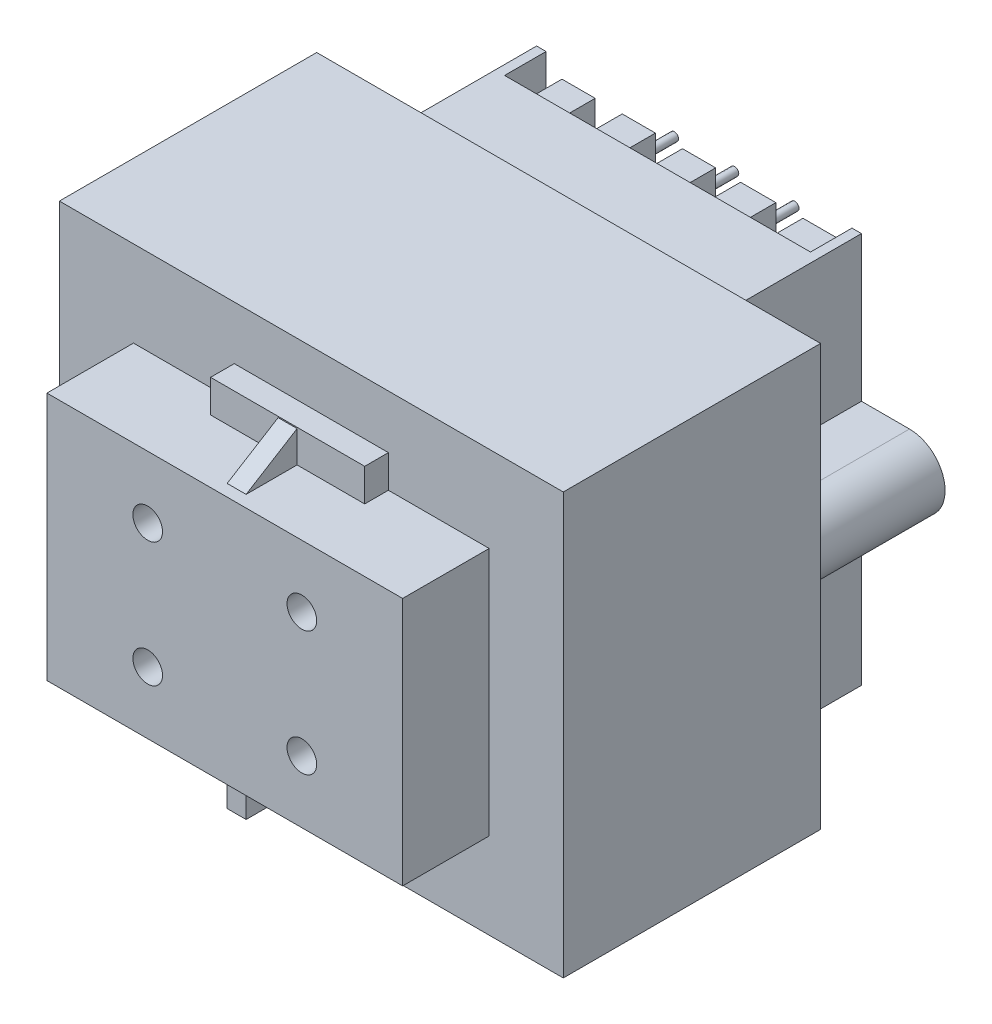
SolidWorks part; units mm, degrees
ref_plane "Спереди" through (0, 0, 0) normal (0, 0, 1) x (1, 0, 0)
ref_plane "Сверху" through (0, 0, 0) normal (0, 1, 0) x (1, 0, 0)
ref_plane "Справа" through (0, 0, 0) normal (1, 0, 0) x (0, 0, -1)
sketch "Эскиз1" plane through (0, 0, 0) normal (0, 0, 1) x (1, 0, 0)
  line L0 (-46.8652, 0) -> (48.3577, 0) construction
  line L1 (0, 0) -> (0, 50.638) construction
  line L3 (-21.25, -17.75) -> (21.25, -17.75)
  line L4 (-21.25, -17.75) -> (-21.25, 17.75)
  line L5 (-21.25, 17.75) -> (21.25, 17.75)
  line L6 (21.25, -17.75) -> (21.25, 17.75)
  dimension "D1" = 42.5
  dimension "D2" = 35.5
extrude "Вытянуть1" add sketch "Эскиз1" along normal blind 40
sketch "Эскиз2" plane through (0, 0, 40) normal (0, 0, 1) x (1, 0, 0)
  line L0 (0, -4.5156) -> (0, 6.793) construction
  line L1 (-5.8899, 0) -> (6.9108, 0) construction
  line L3 (-15, -10.5) -> (15, -10.5)
  line L4 (-21.25, 17.75) -> (-21.25, -17.75)
  line L5 (-21.25, -17.75) -> (21.25, -17.75)
  line L6 (21.25, -17.75) -> (21.25, 17.75)
  line L7 (21.25, 17.75) -> (-21.25, 17.75)
  line L8 (-21.25, 17.75) -> (-21.25, -17.75)
  line L9 (-21.25, -17.75) -> (21.25, -17.75)
  line L10 (21.25, -17.75) -> (21.25, 17.75)
  line L11 (21.25, 17.75) -> (-21.25, 17.75)
  line L12 (-15, -10.5) -> (-15, 10.5)
  line L13 (-15, 10.5) -> (15, 10.5)
  line L14 (15, -10.5) -> (15, 10.5)
  dimension "D2" = 30
  dimension "D3" = 21
  dimension "D1" = 0
extrude "Вырез-Вытянуть1" cut sketch "Эскиз2" against normal blind 7.3
sketch "Эскиз3" plane through (0, 0, 32.7) normal (0, 0, 1) x (1, 0, 0)
  line L0 (0, 0) -> (0, 16.3881) construction
  line L1 (0, 0) -> (13.3068, 0) construction
  line L2 (-6.5, -13.25) -> (6.5, -13.25)
  line L3 (-6.5, -13.25) -> (-6.5, 13.25)
  line L4 (-6.5, 13.25) -> (6.5, 13.25)
  line L5 (6.5, -13.25) -> (6.5, 13.25)
  dimension "D1" = 13
  dimension "D2" = 26.5
extrude "Вытянуть2" add sketch "Эскиз3" along normal blind 2
sketch "Эскиз4" plane through (0, 0, 0) normal (1, 0, 0) x (0, 0, -1)
  line L1 (-34.7, 10.5) -> (-39, 10.5)
  line L2 (-34.7, 10.5) -> (-34.7, 13.1539)
  line L3 (-39, -10.5) -> (-39, -13.25)
  line L4 (-39, -13.25) -> (-34.7, -13.25)
  line L5 (-34.7, -13.25) -> (-34.7, -10.5) construction
  line L6 (-32.7, 10.5) -> (-40, 10.5) construction
  line L7 (-32.7, -10.5) -> (-40, -10.5) construction
  line L8 (-34.7, -10.5) -> (-39, -10.5)
  line L9 (-34.7, -13.25) -> (-34.7, -10.5)
  line L11 (-39, 10.5) -> (-34.7, 13.1539)
extrude "Вытянуть3" add sketch "Эскиз4" along normal blind 0.8 and the other way blind 0.8
sketch "Эскиз5" plane through (0, 0, 40) normal (0, 0, 1) x (1, 0, 0)
  line L0 (0, 0) -> (14.0158, 0) construction
  line L1 (0, 0) -> (0, 9.0803) construction
  circle A0 centre (-6.5, 5.25) radius 1.25
  circle A1 centre (6.5, 5.25) radius 1.25
  circle A2 centre (6.5, -5.25) radius 1.25
  circle A3 centre (-6.5, -5.25) radius 1.25
  dimension "D1" = 2.5
  dimension "D2" = 10.5
  dimension "D3" = 13
extrude "Вырез-Вытянуть2" cut sketch "Эскиз5" against normal blind 2
sketch "Эскиз6" plane through (0, 0, 0) normal (0, 0, -1) x (-1, 0, 0)
  line L0 (-7.8303, 0) -> (7.2418, 0) construction
  line L1 (0, 15.7337) -> (0, -14.6975) construction
  line L2 (-17.75, 4.25) -> (-13.7, 4.25)
  line L3 (-13.7, -16.5) -> (13.7, -16.5)
  line L4 (-13.7, -16.5) -> (-13.7, -1.75)
  line L5 (-13.7, 16.5) -> (13.7, 16.5)
  line L6 (13.7, -16.5) -> (13.7, -1.75)
  line L7 (-17.75, -1.75) -> (-13.7, -1.75)
  line L8 (-13.7, 4.25) -> (-13.7, 16.5)
  line L9 (13.7, 4.25) -> (13.7, 16.5)
  line L10 (21.25, -17.75) -> (21.25, 17.75)
  line L11 (21.25, 17.75) -> (-21.25, 17.75)
  line L12 (-21.25, 17.75) -> (-21.25, -17.75)
  line L13 (-21.25, -17.75) -> (21.25, -17.75)
  line L14 (21.25, -17.75) -> (21.25, 17.75)
  line L15 (21.25, 17.75) -> (-21.25, 17.75)
  line L16 (-21.25, 17.75) -> (-21.25, -17.75)
  line L17 (-21.25, -17.75) -> (21.25, -17.75)
  line L18 (13.7, 4.25) -> (17.75, 4.25)
  line L19 (13.7, -1.75) -> (17.75, -1.75)
  line L20 (-17.75, 1.25) -> (-17.75, 5.963) construction
  arc A0 (-17.75, 4.25) -> (-17.75, -1.75) centre (-17.75, 1.25) ccw
  arc A1 (17.75, -1.75) -> (17.75, 4.25) centre (17.75, 1.25) ccw
  dimension "D4" = 41.5
  dimension "D5" = 6
  dimension "D6" = 13.5
  dimension "D1" = 33
  dimension "D2" = 27.4
  dimension "D3" = 0
extrude "Вырез-Вытянуть3" cut sketch "Эскиз6" against normal blind 11
sketch "Эскиз7" plane through (0, 0, 0) normal (0, 0, -1) x (-1, 0, 0)
  line L0 (-17.75, 1.25) -> (18.26, 1.25) construction
  line L1 (0, 0) -> (0, 11.9161) construction
  line L3 (16, 0) -> (16, 2.5)
  line L4 (-18.5, 0) -> (-16, 0)
  line L5 (-18.5, 0) -> (-18.5, 2.5)
  line L6 (-18.5, 2.5) -> (-16, 2.5)
  line L7 (-16, 0) -> (-16, 2.5)
  line L8 (18.5, 2.5) -> (16, 2.5)
  line L9 (18.5, 0) -> (18.5, 2.5)
  line L10 (18.5, 0) -> (16, 0)
  dimension "D1" = 2.5
  dimension "D2" = 32
extrude "Вырез-Вытянуть4" cut sketch "Эскиз7" against normal blind 8
sketch "Эскиз8" plane through (0, 0, 0) normal (0, 0, -1) x (-1, 0, 0)
  line L0 (-13.7, -16.5) -> (13.7, -16.5) construction
  line L1 (0, 9.0803) -> (0, -16.3881) construction
  line L2 (-13.7, 16.5) -> (-13.7, 4.25) construction
  line L3 (-12.9, 6.25) -> (12.9, 6.25)
  line L4 (-12.9, 6.25) -> (-12.9, 10.5)
  line L5 (-12.9, 10.5) -> (12.9, 10.5)
  line L6 (12.9, 6.25) -> (12.9, 10.5)
  line L7 (13.7, 4.25) -> (13.7, 16.5) construction
  line L8 (-12.9, -10.5) -> (12.9, -10.5)
  line L9 (12.9, -10.5) -> (12.9, -3.75)
  line L10 (-12.9, -3.75) -> (12.9, -3.75)
  line L11 (-12.9, -10.5) -> (-12.9, -3.75)
  line L14 (16, 1.25) -> (1.4009, 1.25) construction
  line L15 (16, 2.5) -> (16, 0) construction
  dimension "D1" = 5
  dimension "D2" = 0.8
  dimension "D3" = 0.8
  dimension "D4" = 10.5
  dimension "D6" = 6
  dimension "D7" = 5
extrude "Вырез-Вытянуть5" cut sketch "Эскиз8" against normal blind 11
sketch "Эскиз9" plane through (0, 0, 0) normal (0, 0, -1) x (-1, 0, 0)
  line L0 (-11.0474, 0) -> (12.9883, 0) construction
  line L1 (0, 0) -> (0, 19.7633) construction
  line L2 (13.7, 16.5) -> (-13.7, 16.5) construction
  line L3 (12.9, 16.5) -> (-12.9, 16.5)
  line L4 (-12.9, 10.5) -> (-12.9, 16.5)
  line L6 (12.1, 15.15) -> (12.1, 10.5)
  line L7 (-12.1, 15.15) -> (12.1, 15.15)
  line L8 (12.1, 10.5) -> (12.9, 10.5)
  line L9 (-12.1, 15.15) -> (-12.1, 10.5)
  line L10 (-12.1, 10.5) -> (-12.9, 10.5)
  line L11 (12.9, 10.5) -> (12.9, 16.5)
  line L12 (12.9, -10.5) -> (12.9, -16.5)
  line L13 (-12.1, -10.5) -> (-12.9, -10.5)
  line L14 (-12.1, -15.15) -> (-12.1, -10.5)
  line L15 (12.1, -10.5) -> (12.9, -10.5)
  line L16 (-12.1, -15.15) -> (12.1, -15.15)
  line L17 (12.1, -15.15) -> (12.1, -10.5)
  line L18 (-12.9, -10.5) -> (-12.9, -16.5)
  line L19 (12.9, -16.5) -> (-12.9, -16.5)
  line L20 (12.9, 10.5) -> (-12.9, 10.5) construction
  point P12 (0, 15.15)
  point P17 (0, -15.15)
  dimension "D1" = 15.15
  dimension "D2" = 0.8
extrude "Вырез-Вытянуть6" cut sketch "Эскиз9" against normal blind 3.5
sketch "Эскиз10" plane through (0, 0, 0) normal (0, 0, -1) x (-1, 0, 0)
  line L0 (0, 0) -> (0, 19.6057) construction
  line L1 (12.9, 10.5) -> (-12.9, 10.5) construction
  line L2 (-3.5, 10.5) -> (-1.4, 10.5)
  line L3 (-3.5, 10.5) -> (-3.5, 15.15)
  line L4 (-3.5, 15.15) -> (-1.4, 15.15)
  line L5 (-1.4, 10.5) -> (-1.4, 15.15)
  line L6 (-12.1, 15.15) -> (12.1, 15.15) construction
  line L7 (12.1, 10.5) -> (-12.1, 10.5) construction
  line L8 (1.4, 10.5) -> (3.68, 10.5)
  line L9 (1.4, 10.5) -> (1.4, 15.15)
  line L10 (1.4, 15.15) -> (3.68, 15.15)
  line L11 (3.68, 10.5) -> (3.68, 15.15)
  line L12 (0, 0) -> (13.4678, 0) construction
  line L13 (6.48, 10.5) -> (8.76, 10.5)
  line L14 (6.48, 10.5) -> (6.48, 15.15)
  line L15 (6.48, 15.15) -> (8.76, 15.15)
  line L16 (8.76, 10.5) -> (8.76, 15.15)
  line L17 (11.56, 15.15) -> (12.5, 15.15)
  line L18 (11.56, 10.5) -> (11.56, 15.15)
  line L19 (12.5, 15.15) -> (12.5, 10.5)
  line L20 (12.5, 10.5) -> (11.56, 10.5)
  line L21 (-12.5, 10.5) -> (-11.56, 10.5)
  line L22 (-12.5, 15.15) -> (-12.5, 10.5)
  line L23 (-11.56, 15.15) -> (-12.5, 15.15)
  line L24 (-11.56, 10.5) -> (-11.56, 15.15)
  line L25 (-8.76, 10.5) -> (-8.76, 15.15)
  line L26 (-6.48, 15.15) -> (-8.76, 15.15)
  line L27 (-6.48, 10.5) -> (-6.48, 15.15)
  line L28 (-6.48, 10.5) -> (-8.76, 10.5)
  line L29 (-6.48, -10.5) -> (-8.76, -10.5)
  line L30 (-6.48, -10.5) -> (-6.48, -15.15)
  line L31 (-6.48, -15.15) -> (-8.76, -15.15)
  line L32 (-8.76, -10.5) -> (-8.76, -15.15)
  line L33 (-11.56, -10.5) -> (-11.56, -15.15)
  line L35 (-11.56, -15.15) -> (-12.5, -15.15)
  line L36 (-12.5, -15.15) -> (-12.5, -10.5)
  line L37 (-12.5, -10.5) -> (-11.56, -10.5)
  line L38 (12.5, -10.5) -> (11.56, -10.5)
  line L40 (12.5, -15.15) -> (12.5, -10.5)
  line L41 (8.76, -10.5) -> (8.76, -15.15)
  line L42 (6.48, -15.15) -> (8.76, -15.15)
  line L43 (6.48, -10.5) -> (6.48, -15.15)
  line L44 (6.48, -10.5) -> (8.76, -10.5)
  line L45 (3.68, -10.5) -> (3.68, -15.15)
  line L46 (1.4, -15.15) -> (3.68, -15.15)
  line L47 (1.4, -10.5) -> (1.4, -15.15)
  line L48 (1.4, -10.5) -> (3.68, -10.5)
  line L49 (-1.4, -10.5) -> (-1.4, -15.15)
  line L50 (-3.5, -15.15) -> (-1.4, -15.15)
  line L51 (-3.5, -10.5) -> (-3.5, -15.15)
  line L52 (-3.5, -10.5) -> (-1.4, -10.5)
  line L53 (11.56, -10.5) -> (11.56, -15.15)
  line L54 (11.56, -15.15) -> (12.5, -15.15)
  dimension "D1" = 2.8
  dimension "D2" = 2.1
  dimension "D3" = 5.08
  dimension "D4" = 2.8
  dimension "D5" = 5.08
  dimension "D6" = 2.8
extrude "Вырез-Вытянуть7" cut sketch "Эскиз10" against normal blind 3.5
sketch "Эскиз11" plane through (0, 0, 0) normal (0, 0, -1) x (-1, 0, 0)
  line L0 (0, 0) -> (14.7247, 0) construction
  line L1 (0, 0) -> (0, 19.4966) construction
  circle A0 centre (0, 12.7) radius 0.35
  circle A1 centre (0, -12.7) radius 0.35
  dimension "D1" = 0.7
  dimension "D2" = 25.4
extrude "Вытянуть4" add sketch "Эскиз11" along normal blind 3
pattern_linear "Линейный массив1" count 3 spacing 5.08 along (1, 0, 0) count 3 spacing 5.08 along (-1, 0, 0) of "Вытянуть4"
sketch "Эскиз12" plane through (0, 0, -3) normal (0, 0, -1) x (-1, 0, 0)
  circle A1 centre (10.16, 12.7) radius 0.35
  circle A2 centre (10.16, 12.7) radius 0.35
  circle A3 centre (10.16, -12.7) radius 0.35
  circle A4 centre (10.16, -12.7) radius 0.35
  circle A5 centre (0, -12.7) radius 0.35
  circle A6 centre (0, -12.7) radius 0.35
  circle A7 centre (-5.08, -12.7) radius 0.35
  circle A8 centre (-5.08, -12.7) radius 0.35
  dimension "D1" = 0
  dimension "D2" = 0
  dimension "D3" = 0
  dimension "D4" = 0
extrude "Вырез-Вытянуть8" cut sketch "Эскиз12" against normal up to surface (3 mm away) up to face at (-10.16, -12.825, 0)
